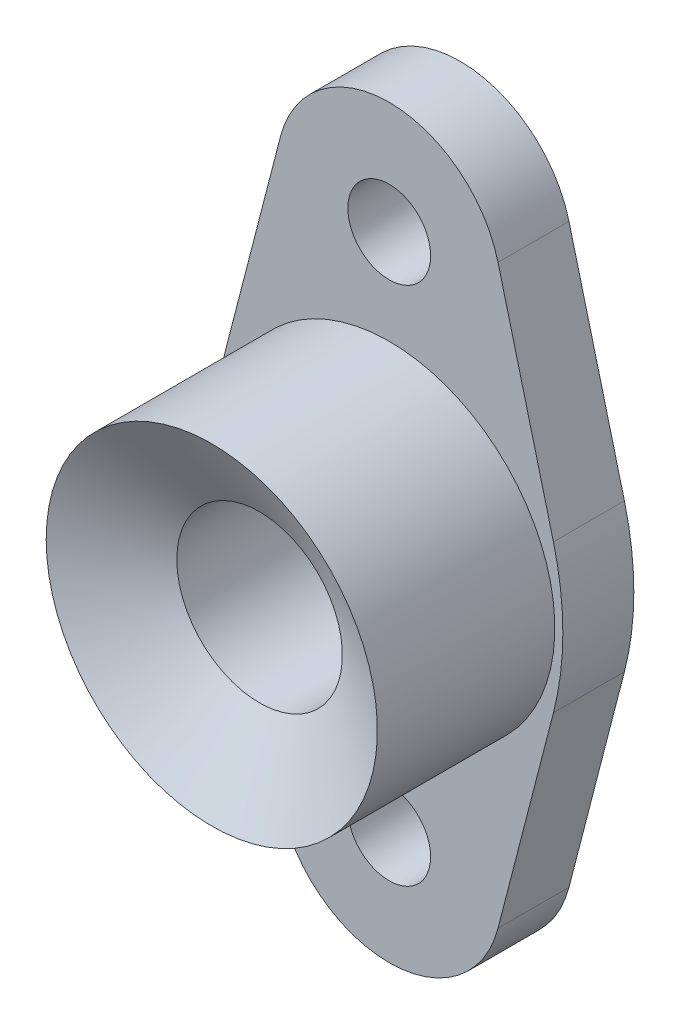
SolidWorks part; units mm, degrees
ref_plane "Front Plane" through (0, 0, 0) normal (0, 0, 1) x (1, 0, 0)
ref_plane "Top Plane" through (0, 0, 0) normal (0, 1, 0) x (1, 0, 0)
ref_plane "Right Plane" through (0, 0, 0) normal (1, 0, 0) x (0, 0, -1)
sketch "Sketch1" plane through (0, 0, 0) normal (0, 0, 1) x (1, 0, 0)
  line L0 (0, 58.4553) -> (0, -64.4564) construction
  line L1 (-72.5016, 0) -> (65.3016, 0) construction
  line L2 (-18.3952, 48.7557) -> (-31, 0)
  line L3 (-31, 0) -> (-18.3952, -48.7557)
  line L4 (18.3952, 48.7557) -> (31, 0)
  line L5 (31, 0) -> (18.3952, -48.7557)
  circle A0 centre (0, 44) radius 7
  arc A1 (18.3952, 48.7557) -> (-18.3952, 48.7557) centre (0, 44) ccw
  circle A2 centre (0, -44) radius 7
  arc A3 (-18.3952, -48.7557) -> (18.3952, -48.7557) centre (0, -44) ccw
  circle A4 centre (0, 0) radius 14
  dimension "D1" = 38
  dimension "D2" = 14
  dimension "D6" = 28
  dimension "D3" = 88
  dimension "D4" = 44
  dimension "D5" = 62
extrude "Boss-Extrude1" add sketch "Sketch1" along normal blind 12
fillet "Fillet1" radius 50 2 edges at (-31, 0, 6) (31, 0, 6)
sketch "Sketch3" plane through (0, 0, 0) normal (0, 1, 0) x (1, 0, 0)
  line L0 (0, 17.4198) -> (0, -36.0784) construction
  line L1 (14, -12) -> (28, -12)
  line L2 (28, -12) -> (28, -42)
  line L3 (28, -42) -> (14, -33.9171)
  line L4 (14, -33.9171) -> (14, -12)
  point P5 (0, 0)
  point P8 (14, -25.8147)
  dimension "D1" = 30
  dimension "D2" = 28
  dimension "D3" = 60
revolve "Revolve1" add sketch "Sketch3" angle 360 about L0
